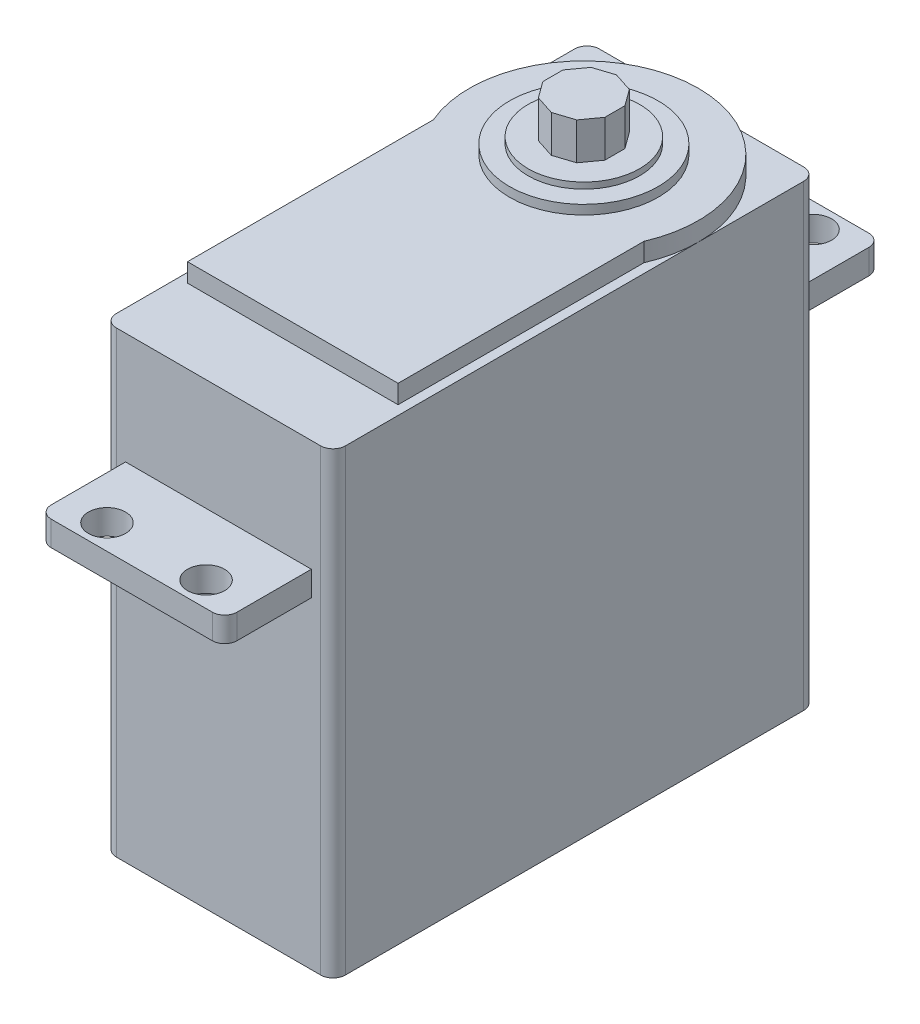
SolidWorks part; units mm, degrees
ref_plane "Front Plane" through (0, 0, 0) normal (0, 0, 1) x (1, 0, 0)
ref_plane "Top Plane" through (0, 0, 0) normal (0, 1, 0) x (1, 0, 0)
ref_plane "Right Plane" through (0, 0, 0) normal (1, 0, 0) x (0, 0, -1)
sketch "Sketch1" plane through (0, 0, 0) normal (0, 1, 0) x (1, 0, 0)
  line L1 (-8.25, 19.5) -> (8.25, 19.5)
  line L2 (-9.25, 18.5) -> (-9.25, -18.5)
  line L3 (-8.25, -19.5) -> (8.25, -19.5)
  line L4 (9.25, 18.5) -> (9.25, -18.5)
  line L5 (-9.25, 19.5) -> (9.25, -19.5) construction
  line L6 (-9.25, -19.5) -> (9.25, 19.5) construction
  arc A0 (8.25, -19.5) -> (9.25, -18.5) centre (8.25, -18.5) ccw
  arc A1 (-9.25, -18.5) -> (-8.25, -19.5) centre (-8.25, -18.5) ccw
  arc A2 (8.25, 19.5) -> (9.25, 18.5) centre (8.25, 18.5) cw
  arc A3 (-8.25, 19.5) -> (-9.25, 18.5) centre (-8.25, 18.5) ccw
  point P0 (0, 0)
  dimension "D3" = 1
  dimension "D1" = 39
  dimension "D2" = 18.5
extrude "Boss-Extrude1" add sketch "Sketch1" along normal blind 37
sketch "Sketch3" plane through (0, 37, 0) normal (0, 1, 0) x (1, 0, 0)
  line L0 (9.25, -18.5) -> (9.25, 18.5) construction
  line L1 (-9.25, 18.5) -> (-9.25, -18.5) construction
  line L3 (0, 10) -> (0, -21) construction
  line L7 (8.5, -13.5) -> (-8.5, -13.5)
  line L8 (-8.5, -13.5) -> (-8.5, 6.3514)
  line L9 (8.5, -13.5) -> (8.5, 6.3514)
  line L10 (-8.25, -19.5) -> (8.25, -19.5) construction
  arc A0 (8.5, 6.3514) -> (-8.5, 6.3514) centre (0, 10) ccw
  dimension "D1" = 17
  dimension "D2" = 6
  dimension "D3" = 23.5
extrude "Boss-Extrude2" add sketch "Sketch3" along normal blind 1.5
sketch "Sketch4" plane through (0, 38.5, 0) normal (0, 1, 0) x (1, 0, 0)
  circle A0 centre (0, 10) radius 6
  dimension "D1" = 12
extrude "Boss-Extrude3" add sketch "Sketch4" along normal blind 0.75
sketch "Sketch5" plane through (0, 39.25, 0) normal (0, 1, 0) x (1, 0, 0)
  circle A0 centre (0, 10) radius 4.5
  dimension "D1" = 9
extrude "Boss-Extrude4" add sketch "Sketch5" along normal blind 0.5
sketch "Sketch6" plane through (0, 39.75, 0) normal (0, 1, 0) x (1, 0, 0)
  line L0 (-2.5, 9.1877) -> (-1.5451, 7.8734)
  line L1 (2.5, 9.1877) -> (2.5, 10.8123)
  line L2 (2.5, 10.8123) -> (1.5451, 12.1266)
  line L3 (1.5451, 12.1266) -> (0, 12.6287)
  line L4 (0, 12.6287) -> (-1.5451, 12.1266)
  line L5 (-1.5451, 12.1266) -> (-2.5, 10.8123)
  line L6 (-2.5, 10.8123) -> (-2.5, 9.1877)
  line L7 (-1.5451, 7.8734) -> (0, 7.3713)
  line L8 (0, 7.3713) -> (1.5451, 7.8734)
  line L9 (1.5451, 7.8734) -> (2.5, 9.1877)
  circle A0 centre (0, 10) radius 2.5 construction
  dimension "D1" = 5
extrude "Boss-Extrude5" add sketch "Sketch6" along normal blind 3
ref_plane "Plane1" through (0, 26, 0) normal (0, -1, 0) x (-1, 0, 0)
sketch "Sketch8" plane through (0, 26, 0) normal (0, -1, 0) x (-1, 0, 0)
  line L0 (-8.25, 19.5) -> (8.25, 19.5) construction
  line L1 (4, -24.5) -> (-4, -24.5) construction
  line L2 (4, -24.5) -> (4, 24.5) construction
  line L3 (4, 24.5) -> (-4, 24.5) construction
  line L4 (-4, -24.5) -> (-4, 24.5) construction
  line L5 (4, -24.5) -> (-4, 24.5) construction
  line L6 (4, 24.5) -> (-4, -24.5) construction
  line L7 (-7.5, 19.5) -> (7.5, 19.5)
  line L8 (-7.5, 19.5) -> (-7.5, 25.5)
  line L9 (-6.5, 26.5) -> (6.5, 26.5)
  line L10 (7.5, 19.5) -> (7.5, 25.5)
  line L11 (-7.5, 19.5) -> (7.5, 26.5) construction
  line L12 (-7.5, 26.5) -> (7.5, 19.5) construction
  line L13 (-9.25, 0) -> (9.25, 0) construction
  line L14 (-9.25, -18.5) -> (-9.25, 18.5) construction
  line L15 (9.25, 18.5) -> (9.25, -18.5) construction
  line L16 (-7.5, -19.5) -> (7.5, -19.5)
  line L17 (7.5, -19.5) -> (7.5, -25.5)
  line L18 (-6.5, -26.5) -> (6.5, -26.5)
  line L19 (-7.5, -19.5) -> (-7.5, -25.5)
  circle A0 centre (-4, 24.5) radius 1.5
  circle A1 centre (4, 24.5) radius 1.5
  circle A2 centre (4, -24.5) radius 1.5
  circle A3 centre (-4, -24.5) radius 1.5
  arc A4 (6.5, 26.5) -> (7.5, 25.5) centre (6.5, 25.5) cw
  arc A5 (-7.5, 25.5) -> (-6.5, 26.5) centre (-6.5, 25.5) cw
  circle A6 centre (4, -24.5) radius 1.5
  arc A7 (6.5, -26.5) -> (7.5, -25.5) centre (6.5, -25.5) ccw
  arc A8 (-7.5, -25.5) -> (-6.5, -26.5) centre (-6.5, -25.5) ccw
  circle A9 centre (-4, -24.5) radius 1.5
  point P0 (0, 0)
  point P15 (0, 23)
  dimension "D3" = 3
  dimension "D6" = 1
  dimension "D1" = 49
  dimension "D2" = 8
  dimension "D4" = 15
  dimension "D5" = 7
extrude "Boss-Extrude6" add sketch "Sketch8" against normal blind 2 contours A5 L8 L7 L10 A4 L9 A1 A0 | L19 A8 L18 A7 L17 L16 A3 A2
